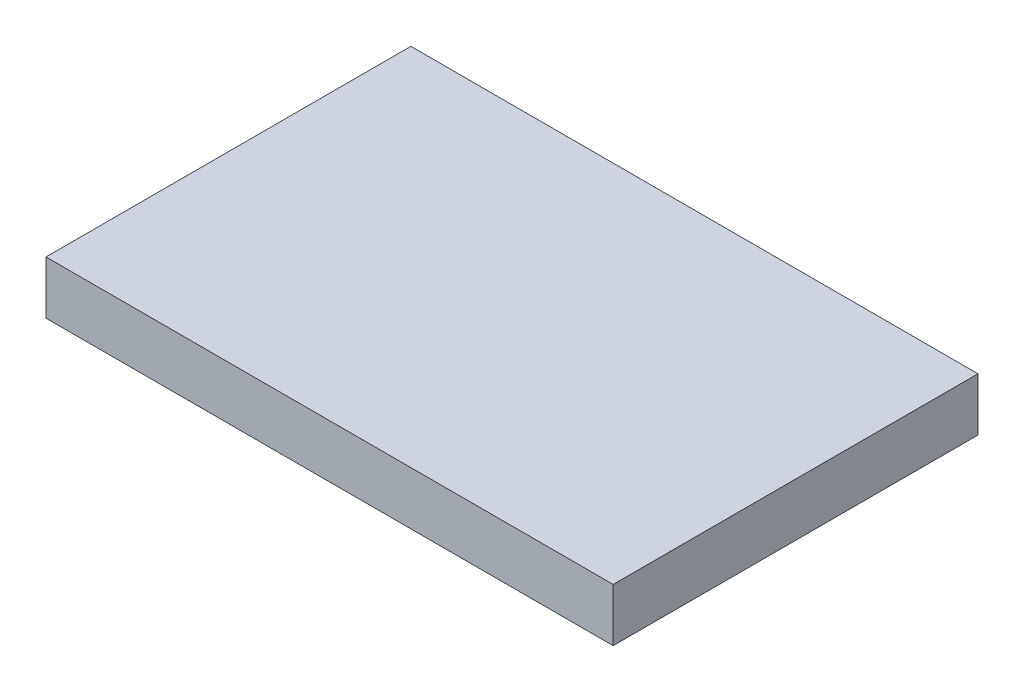
SolidWorks part; units mm, degrees
ref_plane "Front" through (0, 0, 0) normal (0, 0, 1) x (1, 0, 0)
ref_plane "Top" through (0, 0, 0) normal (0, 1, 0) x (1, 0, 0)
ref_plane "Right" through (0, 0, 0) normal (1, 0, 0) x (0, 0, -1)
sketch "Sketch1" plane through (0, 0, 0) normal (0, 1, 0) x (1, 0, 0)
  line L1 (0, 0) -> (81.5, 0)
  line L2 (0, 0) -> (0, -51)
  line L3 (0, -51) -> (81.5, -51)
  line L4 (81.5, 0) -> (81.5, -51)
  dimension "D1" = 81.5
  dimension "D2" = 51
extrude "Boss-Extrude1" add sketch "Sketch1" along normal blind 2
sketch "Sketch2" plane through (0, 2, 0) normal (0, 1, 0) x (1, 0, 0)
  line L0 (-2, 2) -> (-2, -53)
  line L1 (0, 0) -> (81.5, 0)
  line L2 (0, 0) -> (0, -51)
  line L3 (0, -51) -> (81.5, -51)
  line L4 (81.5, 0) -> (81.5, -51)
  line L5 (-2, -53) -> (83.5, -53)
  line L6 (83.5, 2) -> (83.5, -53)
  line L7 (-2, 2) -> (83.5, 2)
  dimension "D1" = 2
extrude "Boss-Extrude2" add sketch "Sketch2" against normal blind 8
